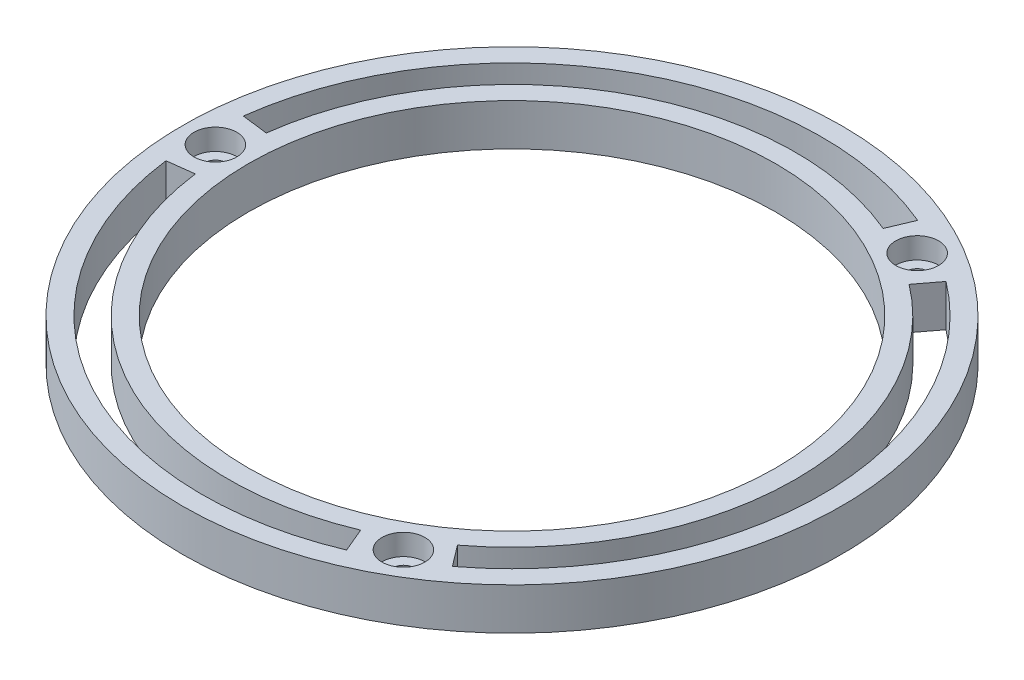
SolidWorks part; units mm, degrees
ref_plane "Front Plane" through (0, 0, 0) normal (0, 0, 1) x (1, 0, 0)
ref_plane "Top Plane" through (0, 0, 0) normal (0, 1, 0) x (1, 0, 0)
ref_plane "Right Plane" through (0, 0, 0) normal (1, 0, 0) x (0, 0, -1)
sketch "Sketch1" plane through (0, 0, 0) normal (0, 1, 0) x (1, 0, 0)
  line L0 (-50, 0) -> (50, 0) construction
  line L1 (-25, 43.3013) -> (25, -43.3013) construction
  line L2 (-25, -43.3013) -> (25, 43.3013) construction
  line L3 (30.2166, 39.8366) -> (24.1733, 31.8693)
  line L4 (19.3913, 46.0866) -> (15.513, 36.8693)
  line L5 (30.2166, -39.8366) -> (24.1733, -31.8693)
  line L6 (19.3913, -46.0866) -> (15.513, -36.8693)
  line L7 (-49.6078, 6.25) -> (-39.6863, 5)
  line L8 (-49.6078, -6.25) -> (-39.6863, -5)
  line L9 (0, 0) -> (15.513, 36.8693) construction
  line L10 (0, 0) -> (24.1733, 31.8693) construction
  line L11 (0, 0) -> (24.1733, -31.8693) construction
  line L12 (0, 0) -> (15.513, -36.8693) construction
  line L13 (0, 0) -> (-39.6863, 5) construction
  line L14 (-39.6863, -5) -> (0, 0) construction
  circle A0 centre (0, 0) radius 50
  circle A1 centre (0, 0) radius 47
  circle A2 centre (0, 0) radius 43
  circle A3 centre (0, 0) radius 40
  point P10 (0, 0)
  point P14 (0, 0)
  point P17 (0, 0)
  dimension "D1" = 100
  dimension "D2" = 3
  dimension "D5" = 60
  dimension "D6" = 60
  dimension "D7" = 5
  dimension "D8" = 5
  dimension "D9" = 5
  dimension "D10" = 5
  dimension "D11" = 5
  dimension "D12" = 5
  dimension "D3" = 4
  dimension "D4" = 3
extrude "Boss-Extrude1" add sketch "Sketch1" along normal blind 6.35 contours A1 L5 A0 L3 | A3 L5 A2 L3 | A3 L6 A2 L5 | A2 L6 A1 L5 | A1 L6 A0 L5 | A1 L8 A0 L6 | A3 L8 A2 L6 | A3 L7 A2 L8 | A2 L7 A1 L8 | A1 L7 A0 L8 | A1 L4 A0 L7 | A3 L4 A2 L7 | A3 L3 A2 L4 | A2 L3 A1 L4 | A1 L3 A0 L4
sketch "Sketch2" plane through (0, 6.35, 0) normal (0, 1, 0) x (1, 0, 0)
  line L1 (25, 43.3013) -> (20, 34.641) construction
  line L2 (20, -34.641) -> (25, -43.3013) construction
  line L3 (0, 0) -> (25.9863, -34.2595) construction
  line L4 (0, 0) -> (-40, 0) construction
  line L6 (0, 0) -> (20, -34.641) construction
  line L7 (-40, 0) -> (-50, 0) construction
  line L8 (0, 0) -> (20, 34.641) construction
  line L9 (0, 0) -> (16.6765, 39.6345) construction
  circle A0 centre (-45, 0) radius 1.65
  circle A1 centre (22.5, -38.9711) radius 1.65
  circle A2 centre (22.5, 38.9711) radius 1.65
  circle A3 centre (0, 0) radius 40 construction
  circle A4 centre (0, 0) radius 50 construction
  dimension "D1" = 3.3
  dimension "D2" = 5
  dimension "D3" = 5
extrude "M3-holes" cut sketch "Sketch2" against normal up to next
sketch "Sketch3" plane through (0, 6.35, 0) normal (0, 1, 0) x (1, 0, 0)
  circle A0 centre (-45, 0) radius 3.25
  circle A1 centre (22.5, 38.9711) radius 3.25
  circle A2 centre (22.5, -38.9711) radius 3.25
  dimension "D1" = 6.5
extrude "Cut-Extrude1" cut sketch "Sketch3" against normal blind 3.2
